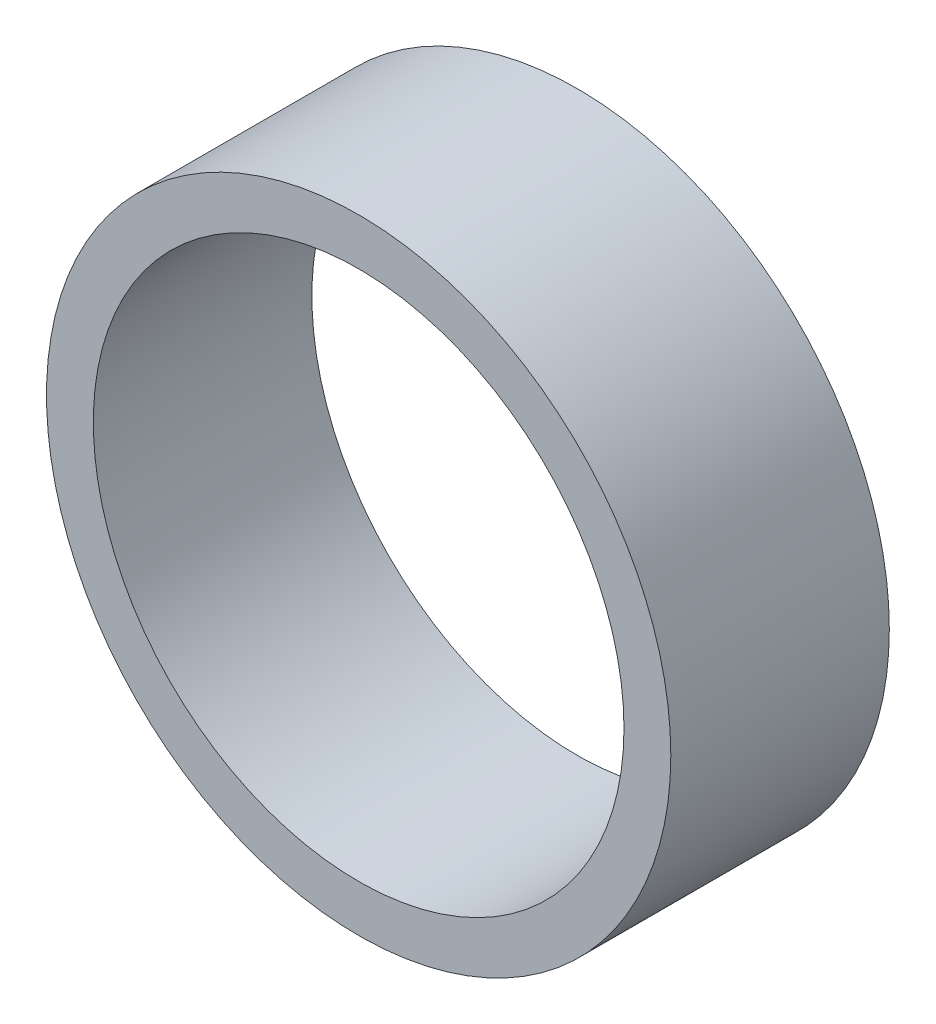
SolidWorks part; units mm, degrees
ref_plane "Front Plane" through (0, 0, 0) normal (0, 0, 1) x (1, 0, 0)
ref_plane "Top Plane" through (0, 0, 0) normal (0, 1, 0) x (1, 0, 0)
ref_plane "Right Plane" through (0, 0, 0) normal (1, 0, 0) x (0, 0, -1)
sketch "Sketch1" plane through (0, 0, 0) normal (0, 0, 1) x (1, 0, 0)
  circle A0 centre (0, 0) radius 8.5
  circle A1 centre (0, 0) radius 10
  dimension "D1" = 17
  dimension "D2" = 20
extrude "Boss-Extrude1" add sketch "Sketch1" along normal blind 7
